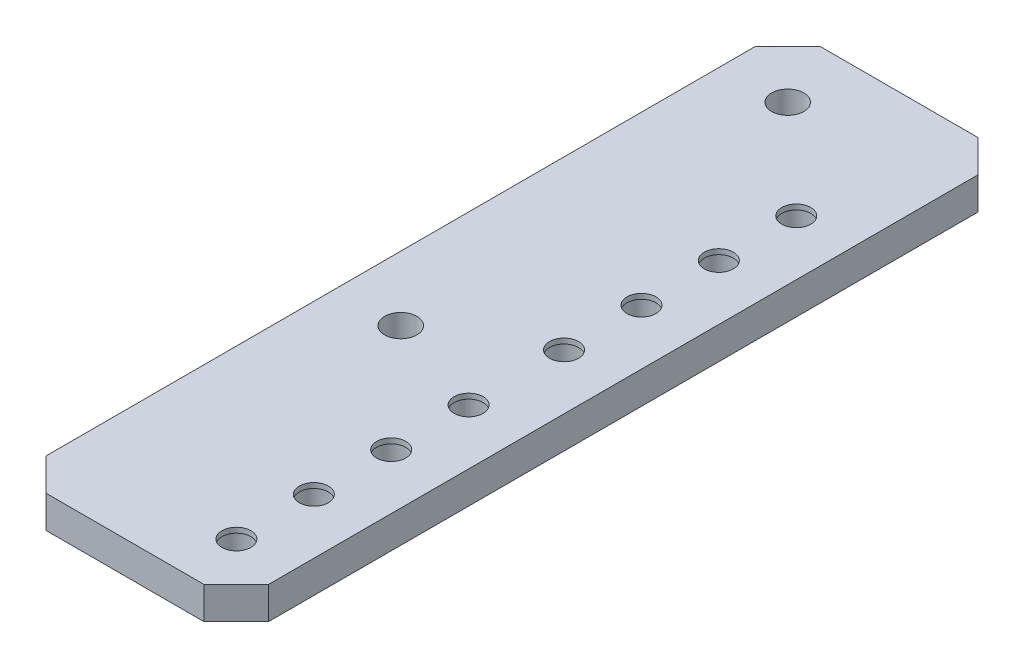
SolidWorks part; units mm, degrees
ref_plane "Front Plane" through (0, 0, 0) normal (0, 0, 1) x (1, 0, 0)
ref_plane "Top Plane" through (0, 0, 0) normal (0, 1, 0) x (1, 0, 0)
ref_plane "Right Plane" through (0, 0, 0) normal (1, 0, 0) x (0, 0, -1)
sketch "Sketch1" plane through (0, 0, 0) normal (0, 1, 0) x (1, 0, 0)
  line L1 (-17.25, -60) -> (17.25, -60)
  line L2 (-17.25, -60) -> (-17.25, 60)
  line L3 (-17.25, 60) -> (17.25, 60)
  line L4 (17.25, -60) -> (17.25, 60)
  line L5 (-17.25, -60) -> (17.25, 60) construction
  line L6 (-17.25, 60) -> (17.25, -60) construction
  point P0 (0, 0)
  dimension "D1" = 120
  dimension "D2" = 34.5
extrude "Boss-Extrude1" add sketch "Sketch1" along normal blind 5
hole_wizard "CBORE for M4 Hex Head Machine Screw2" positions "Sketch2" profile "Sketch4" counterbore size "M4" standard "ANSI Metric"
sketch "Sketch2" plane through (0, 5, 0) normal (0, 1, 0) x (1, 0, 0)
  line L0 (-7.25, 50) -> (-7.25, -10)
  line L1 (-17.25, 60) -> (-17.25, -60) construction
  line L2 (17.25, 60) -> (-17.25, 60) construction
  point P1 (-7.25, 50)
  point P2 (-7.25, -10)
  dimension "D1" = 60
  dimension "D2" = 10
  dimension "10" = 10
sketch "Sketch4" plane through (-7.25, 5, -50) normal (1, 0, 0) x (0, 0, 1)
  line L0 (0, 0) -> (0, 13.3519)
  line L1 (0, 13.3519) -> (2.25, 12)
  line L2 (2.25, 12) -> (2.25, 4.2)
  line L3 (2.25, 4.2) -> (2.5, 4.2)
  line L4 (2.5, 4.2) -> (2.5, 0)
  line L5 (2.5, 0) -> (0, 0)
  line L10 (0, 13.3519) -> (-2.25, 12) construction
  line L11 (0, -6.35) -> (0, 107.95) construction
  dimension "Hole Dia." = 4.5
  dimension "Hole Depth" = 12
  dimension "C'Bore Dia." = 5
  dimension "C'Bore Depth" = 4.2
  dimension "Drill Angle" = 118
hole_wizard "CBORE for M4 Hex Head Machine Screw3" positions "Sketch5" profile "Sketch6" counterbore size "M4" standard "ANSI Metric"
sketch "Sketch5" plane through (0, 0, 0) normal (0, -1, 0) x (-1, 0, 0)
  line L0 (-8.672, 35.4) -> (-8.672, -15.4)
  line L2 (-20.25, 25.5123) -> (-20.25, -36.4731)
  line L4 (-30.25, 54.8042) -> (-30.25, -48.6623)
  line L6 (-0.75, 27.0241) -> (-0.75, -38.3629)
  line L7 (17.25, 60) -> (17.25, -60) construction
  circle A0 centre (7.25, -10) radius 2.25 construction
  point P1 (-8.672, 35.4)
  point P2 (-8.672, -15.4)
  point P25 (-8.672, 10)
  dimension "D1" = 50.8
  dimension "D2" = 37.5
  dimension "D3" = 10
  dimension "D4" = 19.5
  dimension "D5" = 7.922
  dimension "D6" = 10
  dimension "D7" = 15.922
  dimension "D8" = 37.5
sketch "Sketch6" plane through (8.672, 0, -35.4) normal (1, 0, 0) x (0, 0, -1)
  line L0 (0, 0) -> (0, 13.3519)
  line L1 (0, 13.3519) -> (2.25, 12)
  line L2 (2.25, 12) -> (2.25, 4.2)
  line L3 (2.25, 4.2) -> (2.5, 4.2)
  line L4 (2.5, 4.2) -> (2.5, 0)
  line L5 (2.5, 0) -> (0, 0)
  line L10 (0, 13.3519) -> (-2.25, 12) construction
  line L11 (0, -6.35) -> (0, 107.95) construction
  dimension "Hole Dia." = 4.5
  dimension "Hole Depth" = 12
  dimension "C'Bore Dia." = 5
  dimension "C'Bore Depth" = 4.2
  dimension "Drill Angle" = 118
pattern_linear "LPattern1" count 4 spacing 12 along (0, 0, 1) of "CBORE for M4 Hex Head Machine Screw3"
chamfer "Chamfer1" distance 5 angle 45 4 edges at (17.25, 2.5, -60) (17.25, 2.5, 60) (-17.25, 2.5, 60) (-17.25, 2.5, -60)
